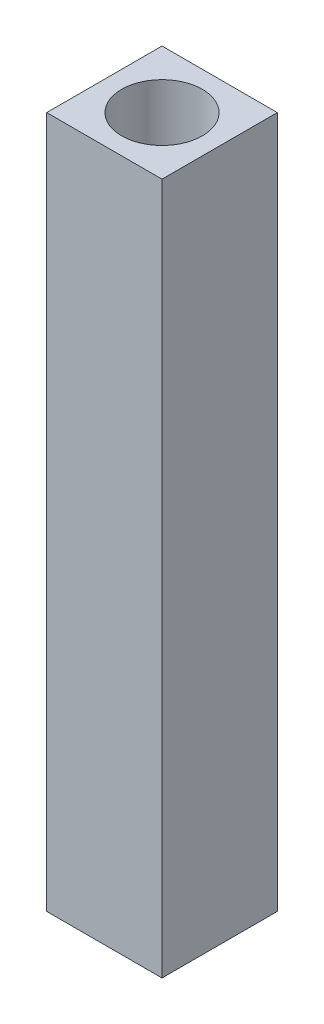
SolidWorks part; units mm, degrees
ref_plane "Front Plane" through (0, 0, 0) normal (0, 0, 1) x (1, 0, 0)
ref_plane "Top Plane" through (0, 0, 0) normal (0, 1, 0) x (1, 0, 0)
ref_plane "Right Plane" through (0, 0, 0) normal (1, 0, 0) x (0, 0, -1)
sketch "Sketch1" plane through (0, 0, 0) normal (0, 1, 0) x (1, 0, 0)
  line L1 (-5, 5) -> (5, 5)
  line L2 (-5, 5) -> (-5, -5)
  line L3 (-5, -5) -> (5, -5)
  line L4 (5, 5) -> (5, -5)
  line L5 (-5, 5) -> (5, -5) construction
  line L6 (-5, -5) -> (5, 5) construction
  circle A0 centre (0, 0) radius 3.5
  point P0 (0, 0)
extrude "Boss-Extrude1" add sketch "Sketch1" along normal blind 60
sketch "Sketch2" plane through (0, 0, 0) normal (0, 1, 0) x (1, 0, 0)
  circle A0 centre (0, 0) radius 3.5
extrude "Boss-Extrude2" add sketch "Sketch2" along normal blind 40
